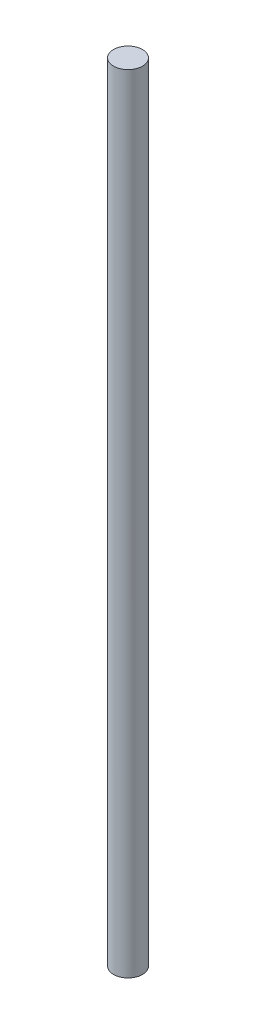
SolidWorks part; units mm, degrees
ref_plane "Front Plane" through (0, 0, 0) normal (0, 0, 1) x (1, 0, 0)
ref_plane "Top Plane" through (0, 0, 0) normal (0, 1, 0) x (1, 0, 0)
ref_plane "Right Plane" through (0, 0, 0) normal (1, 0, 0) x (0, 0, -1)
sketch "Sketch3" plane through (0, 0, 0) normal (0, 0, 1) x (1, 0, 0)
  line L0 (0, 0) -> (0, 50.8) construction
  line L1 (0, 50.8) -> (-0.9271, 50.8)
  line L2 (-0.9271, 50.8) -> (-0.9271, 0.384)
  line L3 (-0.9271, 0.384) -> (0, 0)
  line L4 (0, 0) -> (0, 50.8)
  dimension "D1" = 1.8542
  dimension "D2" = 67.5
  dimension "D3" = 50.8
revolve "Revolve2" add sketch "Sketch3" angle 360 about L0
sketch "Sketch4" plane through (0, 0, 0) normal (0, 0, 1) x (1, 0, 0)
  line L0 (0, 0) -> (0, 1.3111) construction
  line L1 (0, 1.3111) -> (0, 9.1186) construction
  circle A0 centre (0, 1.3111) radius 1.3111 construction
  circle A1 centre (0, 9.1186) radius 9.1186
  dimension "D1" = 18.2372
